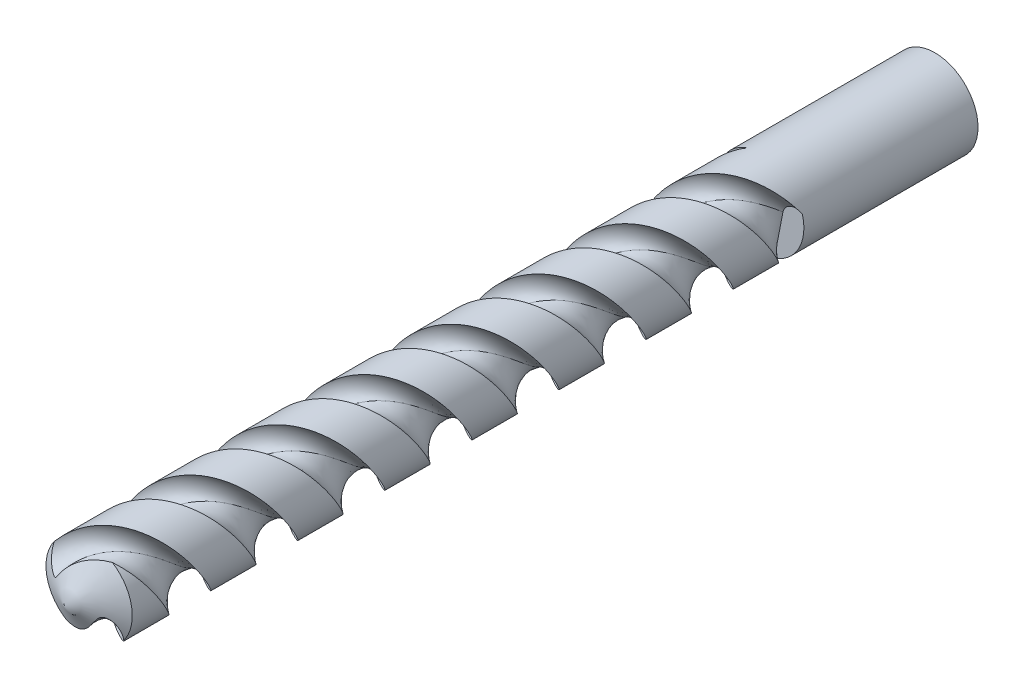
SolidWorks part; units mm, degrees
ref_plane "Front Plane" through (0, 0, 0) normal (0, 0, 1) x (1, 0, 0)
ref_plane "Top Plane" through (0, 0, 0) normal (0, 1, 0) x (1, 0, 0)
ref_plane "Right Plane" through (0, 0, 0) normal (1, 0, 0) x (0, 0, -1)
sketch "Sketch1" plane through (0, 0, 0) normal (0, 0, 1) x (1, 0, 0)
  line L0 (0, -55) -> (0, 55) construction
  circle A0 centre (0, -0.0198) radius 4.95
  dimension "D1" = 9.9
extrude "Boss-Extrude3" add sketch "Sketch1" along normal blind 100 contours A0
sketch "Sketch5" plane through (0, 0, 100) normal (0, 0, 1) x (1, 0, 0)
  circle A1 centre (0, -0.0198) radius 4.95
  circle A2 centre (0, -0.0198) radius 4.95
  dimension "D1" = 0
curve "Helix/Spiral1" pitch 20 height 80 turns 4
sketch "Sketch8" plane through (0, 0, 100) normal (0, 0, 1) x (1, 0, 0)
  line L0 (-2.5513, -0.4089) -> (-1.5653, 4.6762)
  arc A0 (-4.7816, 1.2605) -> (-2.5513, -0.4089) centre (-4, -0.0198) ccw
  circle A1 centre (0, -0.0198) radius 4.95 construction
  circle A2 centre (0, -0.0198) radius 4.95
  arc A3 (-1.5653, 4.6762) -> (-4.7816, 1.2605) centre (0, -0.0198) ccw
  dimension "D3" = 3
  dimension "D1" = 4
  dimension "D2" = 0
sweep "Cut-Sweep1" cut profiles "Sketch8" path "Helix/Spiral1"
pattern_circular "CirPattern1" count 2 over 360 about axis through (0, -0.0198, 0) along (0, 0, 1) of "Cut-Sweep1"
sketch "Sketch13" plane through (0, 0, 0) normal (0, 1, 0) x (1, 0, 0)
  line L0 (-0.007, -100) -> (5.0137, -97.1013)
  line L1 (-1.5653, -100) -> (4.7816, -100) construction
  line L2 (5.0137, -97.1013) -> (5.0137, -102)
  line L3 (5.0137, -102) -> (-0.007, -102)
  line L4 (-0.007, -102) -> (-0.007, -100)
  dimension "D1" = 30
  dimension "D2" = 2
revolve "Cut-Revolve4" cut sketch "Sketch13" angle 360 about L4
